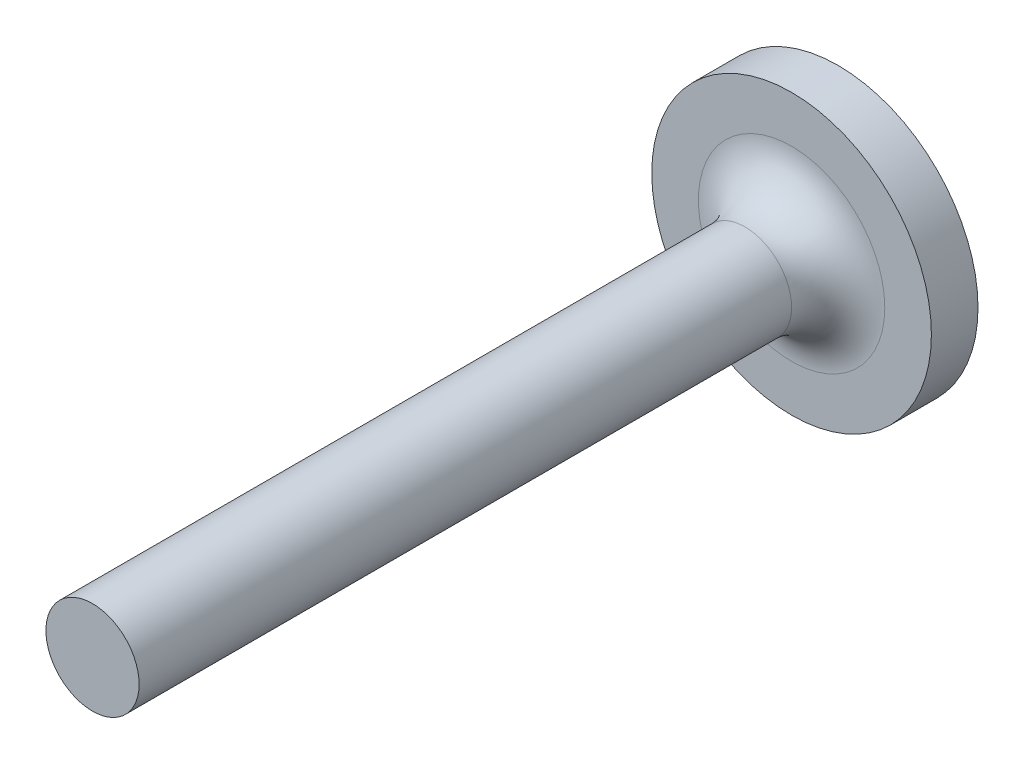
SolidWorks part; units mm, degrees
ref_plane "Front Plane" through (0, 0, 0) normal (0, 0, 1) x (1, 0, 0)
ref_plane "Top Plane" through (0, 0, 0) normal (0, 1, 0) x (1, 0, 0)
ref_plane "Right Plane" through (0, 0, 0) normal (1, 0, 0) x (0, 0, -1)
sketch "Sketch1" plane through (0, 0, 0) normal (0, 0, 1) x (1, 0, 0)
  circle A0 centre (0, 0) radius 6
extrude "Boss-Extrude1" add sketch "Sketch1" along normal blind 2
sketch "Sketch2" plane through (0, 0, 2) normal (0, 0, 1) x (1, 0, 0)
  circle A0 centre (0, 0) radius 2
extrude "Boss-Extrude2" add sketch "Sketch2" along normal blind 35
fillet "Fillet1" radius 2 1 edges at (2, 0, 2)
sketch "Sketch4" plane through (0, 0, 37) normal (0, 0, 1) x (1, 0, 0)
  circle A0 centre (0, 0) radius 2
extrude "Cut-Extrude1" cut sketch "Sketch4" against normal blind 5
